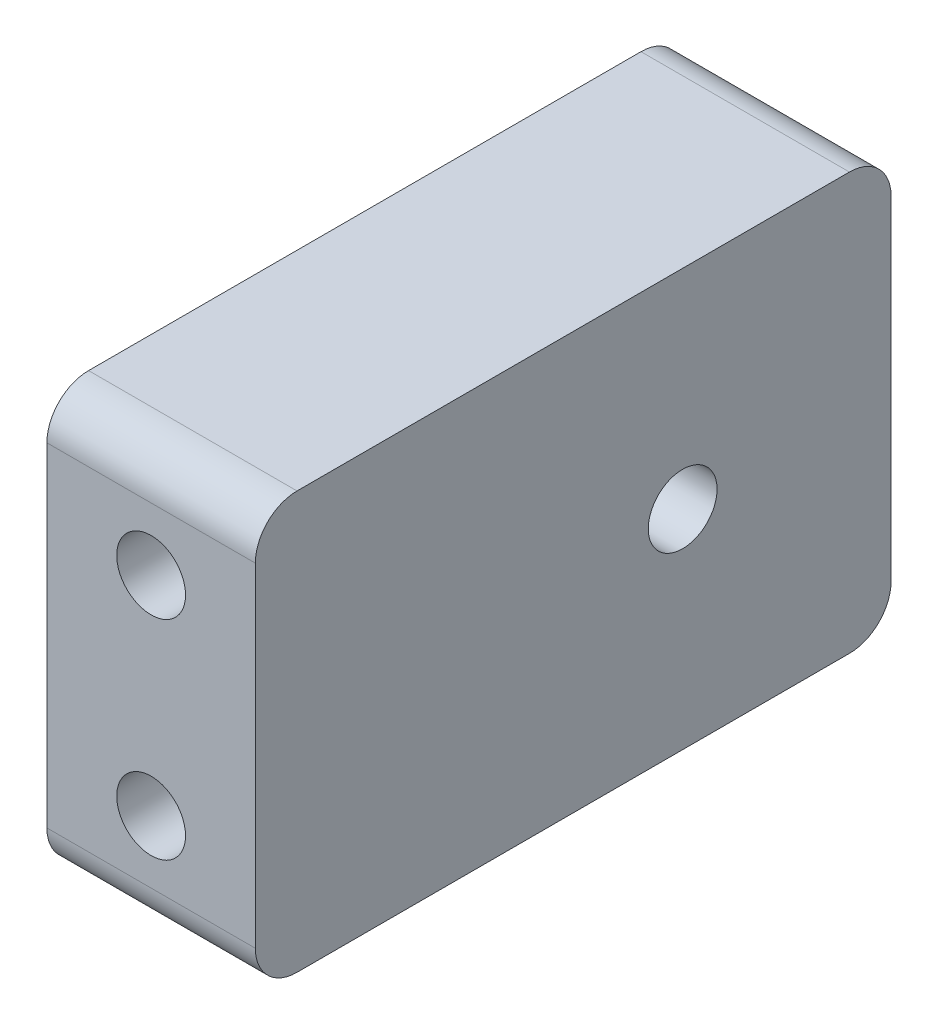
SolidWorks part; units mm, degrees
material "5052-H34"
ref_plane "正面" through (0, 0, 0) normal (0, 0, 1) x (1, 0, 0)
ref_plane "平面" through (0, 0, 0) normal (0, 1, 0) x (1, 0, 0)
ref_plane "右側面" through (0, 0, 0) normal (1, 0, 0) x (0, 0, -1)
sketch "ｽｹｯﾁ1" plane through (0, 0, 0) normal (1, 0, 0) x (0, 0, -1)
  line L0 (30.5, 10) -> (0, 10) construction
  line L1 (0, 0) -> (30.5, 0)
  line L2 (0, 0) -> (0, 20)
  line L3 (0, 20) -> (30.5, 20)
  line L4 (30.5, 0) -> (30.5, 20)
  circle A0 centre (20.5, 10) radius 1.65
  dimension "D3" = 3.3
  dimension "D4" = 20.5
  dimension "D1" = 20
  dimension "D2" = 30.5
extrude "ﾎﾞｽ - 押し出し1" add sketch "ｽｹｯﾁ1" along normal blind 10
hole_wizard "M4x0.7 ねじ穴1" positions "ｽｹｯﾁ5" profile "ｽｹｯﾁ6" tap size "M4x0.7" standard "JIS"
sketch "ｽｹｯﾁ5" plane through (0, 0, 0) normal (0, 0, 1) x (1, 0, 0)
  line L0 (5, 20) -> (5, 0) construction
  line L1 (10, 20) -> (0, 20) construction
  line L2 (10, 0) -> (0, 0) construction
  line L5 (10, 10) -> (0, 10) construction
  line L6 (10, 20) -> (10, 0) construction
  line L7 (0, 20) -> (0, 0) construction
  point P18 (5, 15)
  point P21 (5, 5)
  dimension "D1" = 5
sketch "ｽｹｯﾁ6" plane through (5, 5, 0) normal (1, 0, 0) x (0, -1, 0)
  line L0 (0, 0) -> (0, 15.9914)
  line L1 (0, 15.9914) -> (1.65, 15)
  line L2 (1.65, 15) -> (1.65, 0)
  line L5 (1.65, 0) -> (0, 0)
  line L10 (0, 15.9914) -> (-1.65, 15) construction
  line L11 (0, -6.35) -> (0, 107.95) construction
  dimension "ねじ下穴ﾄﾞﾘﾙ直径" = 3.3
  dimension "ねじ下穴ﾄﾞﾘﾙの深さ" = 15
  dimension "ﾄﾞﾘﾙ角度" = 118
fillet "ﾌｨﾚｯﾄ1" radius 2 4 edges at (5, 0, -30.5) (5, 20, -30.5) (5, 0, 0) (5, 20, 0)
